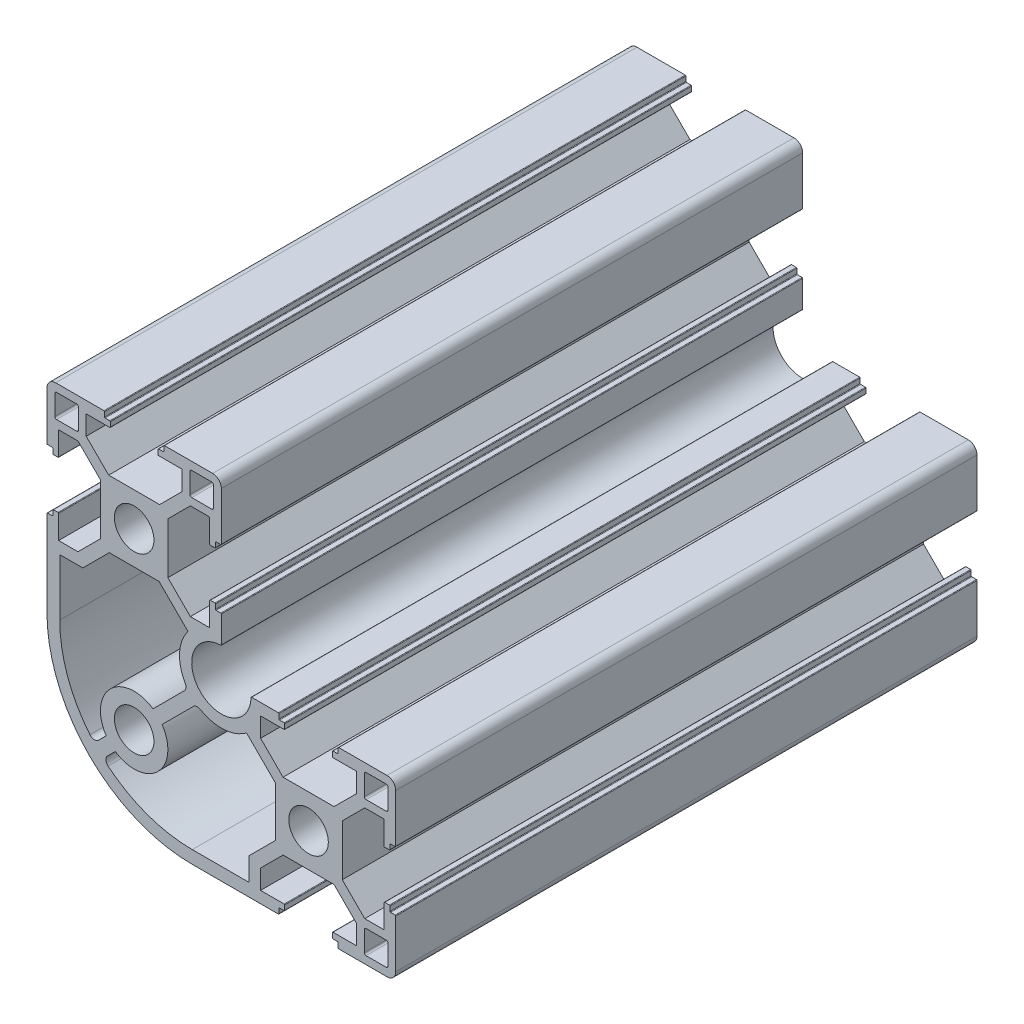
SolidWorks part; units mm, degrees
ref_plane "前视基准面" through (0, 0, 0) normal (0, 0, 1) x (1, 0, 0)
ref_plane "上视基准面" through (0, 0, 0) normal (0, 1, 0) x (1, 0, 0)
ref_plane "右视基准面" through (0, 0, 0) normal (1, 0, 0) x (0, 0, -1)
sketch "草图1" plane through (0, 0, 0) normal (0, 0, 1) x (1, 0, 0)
  line B0 (18.3418, 53.7695) -> (14.8918, 53.7695)
  line B1 (14.5918, 54.0695) -> (14.5918, 57.5195)
  line B2 (14.8918, 57.8195) -> (18.3418, 57.8195)
  line B3 (18.6418, 57.5195) -> (18.6418, 54.0695)
  line B4 (-8.6582, 54.0695) -> (-8.6582, 57.5195)
  line B5 (-8.3582, 57.8195) -> (-4.9082, 57.8195)
  line B6 (-4.6082, 57.5195) -> (-4.6082, 54.0695)
  line B7 (-4.9082, 53.7695) -> (-8.3582, 53.7695)
  line B8 (13.6091, 24.3425) -> (8.2408, 18.9742)
  line B9 (0.1872, 10.9206) -> (-1.1292, 9.6041)
  line B10 (-7.8082, 24.1695) -> (-7.8082, 33.9195)
  line B11 (-7.8082, 33.9195) -> (-3.844, 33.9195)
  line B12 (-3.844, 33.9195) -> (0.706, 38.4695)
  line B13 (0.706, 38.4695) -> (9.2776, 38.4695)
  line B14 (9.2776, 38.4695) -> (14.2429, 33.5043)
  line B15 (24.3265, 23.4206) -> (29.2918, 18.4553)
  line B16 (29.2918, 18.4553) -> (29.2918, 9.8838)
  line B17 (29.2918, 9.8838) -> (24.7418, 5.3338)
  line B18 (24.7418, 5.3338) -> (24.7418, 1.3695)
  line B19 (24.7418, 1.3695) -> (14.9918, 1.3695)
  line B20 (0.4264, 8.0485) -> (1.7429, 9.3649)
  line B21 (9.7964, 17.4185) -> (15.1647, 22.7868)
  line B22 (48.3418, 0.5195) -> (44.8918, 0.5195)
  line B23 (44.5918, 0.8195) -> (44.5918, 4.2695)
  line B24 (44.8918, 4.5695) -> (48.3418, 4.5695)
  line B25 (48.6418, 4.2695) -> (48.6418, 0.8195)
  line B26 (48.3418, 23.7695) -> (44.8918, 23.7695)
  line B27 (44.5918, 24.0695) -> (44.5918, 27.5195)
  line B28 (44.8918, 27.8195) -> (48.3418, 27.8195)
  line B29 (48.6418, 27.5195) -> (48.6418, 24.0695)
  line B30 (19.9918, 34.3686) -> (19.9918, 38.9695)
  line B31 (19.8918, 39.0695) -> (19.0918, 39.0695)
  line B32 (18.9918, 39.1695) -> (18.9918, 39.9695)
  line B33 (18.8918, 40.0695) -> (18.0918, 40.0695)
  line B34 (17.9918, 39.9695) -> (17.9918, 35.9195)
  line B35 (17.9918, 35.9195) -> (14.656, 35.9195)
  line B36 (14.656, 35.9195) -> (10.7918, 39.7838)
  line B37 (10.7918, 39.7838) -> (10.7918, 48.5553)
  line B38 (10.7918, 48.5553) -> (14.656, 52.4195)
  line B39 (14.656, 52.4195) -> (17.9918, 52.4195)
  line B40 (17.9918, 52.4195) -> (17.9918, 48.3695)
  line B41 (18.0918, 48.2695) -> (18.8918, 48.2695)
  line B42 (18.9918, 48.3695) -> (18.9918, 49.1695)
  line B43 (19.0918, 49.2695) -> (19.8918, 49.2695)
  line B44 (19.9918, 49.3695) -> (19.9918, 57.6695)
  line B45 (18.4918, 59.1695) -> (10.1918, 59.1695)
  line B46 (10.0918, 59.0695) -> (10.0918, 58.2695)
  line B47 (9.9918, 58.1695) -> (9.1918, 58.1695)
  line B48 (9.0918, 58.0695) -> (9.0918, 57.2695)
  line B49 (9.1918, 57.1695) -> (13.2418, 57.1695)
  line B50 (13.2418, 57.1695) -> (13.2418, 53.8338)
  line B51 (13.2418, 53.8338) -> (9.3776, 49.9695)
  line B52 (9.3776, 49.9695) -> (0.606, 49.9695)
  line B53 (0.606, 49.9695) -> (-3.2582, 53.8338)
  line B54 (-3.2582, 53.8338) -> (-3.2582, 57.1695)
  line B55 (-3.2582, 57.1695) -> (0.7918, 57.1695)
  line B56 (0.8918, 57.2695) -> (0.8918, 58.0695)
  line B57 (0.7918, 58.1695) -> (-0.0082, 58.1695)
  line B58 (-0.1082, 58.2695) -> (-0.1082, 59.0695)
  line B59 (-0.2082, 59.1695) -> (-8.5082, 59.1695)
  line B60 (-10.0082, 57.6695) -> (-10.0082, 49.3695)
  line B61 (-9.9082, 49.2695) -> (-9.1082, 49.2695)
  line B62 (-9.0082, 49.1695) -> (-9.0082, 48.3695)
  line B63 (-8.9082, 48.2695) -> (-8.1082, 48.2695)
  line B64 (-8.0082, 48.3695) -> (-8.0082, 52.4195)
  line B65 (-8.0082, 52.4195) -> (-4.6724, 52.4195)
  line B66 (-4.6724, 52.4195) -> (-0.8082, 48.5553)
  line B67 (-0.8082, 48.5553) -> (-0.8082, 39.7838)
  line B68 (-0.8082, 39.7838) -> (-4.6724, 35.9195)
  line B69 (-4.6724, 35.9195) -> (-8.0082, 35.9195)
  line B70 (-8.0082, 35.9195) -> (-8.0082, 39.9695)
  line B71 (-8.1082, 40.0695) -> (-8.9082, 40.0695)
  line B72 (-9.0082, 39.9695) -> (-9.0082, 39.1695)
  line B73 (-9.1082, 39.0695) -> (-9.9082, 39.0695)
  line B74 (-10.0082, 38.9695) -> (-10.0082, 24.1695)
  line B75 (14.9918, -0.8305) -> (29.7918, -0.8305)
  line B76 (29.8918, -0.7305) -> (29.8918, 0.0695)
  line B77 (29.9918, 0.1695) -> (30.7918, 0.1695)
  line B78 (30.8918, 0.2695) -> (30.8918, 1.0695)
  line B79 (30.7918, 1.1695) -> (26.7418, 1.1695)
  line B80 (26.7418, 1.1695) -> (26.7418, 4.5053)
  line B81 (26.7418, 4.5053) -> (30.606, 8.3695)
  line B82 (30.606, 8.3695) -> (39.3776, 8.3695)
  line B83 (39.3776, 8.3695) -> (43.2418, 4.5053)
  line B84 (43.2418, 4.5053) -> (43.2418, 1.1695)
  line B85 (43.2418, 1.1695) -> (39.1918, 1.1695)
  line B86 (39.0918, 1.0695) -> (39.0918, 0.2695)
  line B87 (39.1918, 0.1695) -> (39.9918, 0.1695)
  line B88 (40.0918, 0.0695) -> (40.0918, -0.7305)
  line B89 (40.1918, -0.8305) -> (48.4918, -0.8305)
  line B90 (49.9918, 0.6695) -> (49.9918, 8.9695)
  line B91 (49.8918, 9.0695) -> (49.0918, 9.0695)
  line B92 (48.9918, 9.1695) -> (48.9918, 9.9695)
  line B93 (48.8918, 10.0695) -> (48.0918, 10.0695)
  line B94 (47.9918, 9.9695) -> (47.9918, 5.9195)
  line B95 (47.9918, 5.9195) -> (44.656, 5.9195)
  line B96 (44.656, 5.9195) -> (40.7918, 9.7838)
  line B97 (40.7918, 9.7838) -> (40.7918, 18.5553)
  line B98 (40.7918, 18.5553) -> (44.656, 22.4195)
  line B99 (44.656, 22.4195) -> (47.9918, 22.4195)
  line B100 (47.9918, 22.4195) -> (47.9918, 18.3695)
  line B101 (48.0918, 18.2695) -> (48.8918, 18.2695)
  line B102 (48.9918, 18.3695) -> (48.9918, 19.1695)
  line B103 (49.0918, 19.2695) -> (49.8918, 19.2695)
  line B104 (49.9918, 19.3695) -> (49.9918, 27.6695)
  line B105 (48.4918, 29.1695) -> (40.1918, 29.1695)
  line B106 (40.0918, 29.0695) -> (40.0918, 28.2695)
  line B107 (39.9918, 28.1695) -> (39.1918, 28.1695)
  line B108 (39.0918, 28.0695) -> (39.0918, 27.2695)
  line B109 (39.1918, 27.1695) -> (43.2418, 27.1695)
  line B110 (43.2418, 27.1695) -> (43.2418, 23.8338)
  line B111 (43.2418, 23.8338) -> (39.3776, 19.9695)
  line B112 (39.3776, 19.9695) -> (30.606, 19.9695)
  line B113 (30.606, 19.9695) -> (26.7418, 23.8338)
  line B114 (26.7418, 23.8338) -> (26.7418, 27.1695)
  line B115 (26.7418, 27.1695) -> (30.7918, 27.1695)
  line B116 (30.8918, 27.2695) -> (30.8918, 28.0695)
  line B117 (30.7918, 28.1695) -> (29.9918, 28.1695)
  line B118 (29.8918, 28.2695) -> (29.8918, 29.0695)
  line B119 (29.7918, 29.1695) -> (25.1909, 29.1695)
  arc B120 (18.3418, 53.7695) -> (18.6418, 54.0695) centre (18.3418, 54.0695) ccw
  arc B121 (14.5918, 54.0695) -> (14.8918, 53.7695) centre (14.8918, 54.0695) ccw
  arc B122 (14.8918, 57.8195) -> (14.5918, 57.5195) centre (14.8918, 57.5195) ccw
  arc B123 (18.6418, 57.5195) -> (18.3418, 57.8195) centre (18.3418, 57.5195) ccw
  arc B124 (-8.6582, 54.0695) -> (-8.3582, 53.7695) centre (-8.3582, 54.0695) ccw
  arc B125 (-8.3582, 57.8195) -> (-8.6582, 57.5195) centre (-8.3582, 57.5195) ccw
  arc B126 (-4.6082, 57.5195) -> (-4.9082, 57.8195) centre (-4.9082, 57.5195) ccw
  arc B127 (-4.9082, 53.7695) -> (-4.6082, 54.0695) centre (-4.9082, 54.0695) ccw
  circle B128 centre (4.9918, 44.1695) radius 3.4
  circle B129 centre (4.9918, 14.1695) radius 3.4
  arc B130 (14.2429, 33.5043) -> (13.7666, 25.552) centre (19.9918, 29.1695) ccw
  arc B131 (13.6091, 24.3425) -> (13.7666, 25.552) centre (12.902, 25.0496) ccw
  arc B132 (8.2408, 18.9742) -> (0.1872, 10.9206) centre (4.9918, 14.1695) ccw
  arc B133 (-2.6083, 9.6755) -> (-1.1292, 9.6041) centre (-1.8363, 10.3112) ccw
  arc B134 (-7.8082, 24.1695) -> (-2.6083, 9.6755) centre (14.9918, 24.1695) ccw
  arc B135 (16.3743, 22.9443) -> (24.3265, 23.4206) centre (19.9918, 29.1695) ccw
  arc B136 (0.4978, 6.5695) -> (14.9918, 1.3695) centre (14.9918, 24.1695) ccw
  arc B137 (0.4264, 8.0485) -> (0.4978, 6.5695) centre (1.1335, 7.3414) ccw
  arc B138 (1.7429, 9.3649) -> (9.7964, 17.4185) centre (4.9918, 14.1695) ccw
  arc B139 (16.3743, 22.9443) -> (15.1647, 22.7868) centre (15.8718, 22.0797) ccw
  circle B140 centre (34.9918, 14.1695) radius 3.4
  arc B141 (48.3418, 0.5195) -> (48.6418, 0.8195) centre (48.3418, 0.8195) ccw
  arc B142 (44.5918, 0.8195) -> (44.8918, 0.5195) centre (44.8918, 0.8195) ccw
  arc B143 (44.8918, 4.5695) -> (44.5918, 4.2695) centre (44.8918, 4.2695) ccw
  arc B144 (48.6418, 4.2695) -> (48.3418, 4.5695) centre (48.3418, 4.2695) ccw
  arc B145 (48.3418, 23.7695) -> (48.6418, 24.0695) centre (48.3418, 24.0695) ccw
  arc B146 (44.5918, 24.0695) -> (44.8918, 23.7695) centre (44.8918, 24.0695) ccw
  arc B147 (44.8918, 27.8195) -> (44.5918, 27.5195) centre (44.8918, 27.5195) ccw
  arc B148 (48.6418, 27.5195) -> (48.3418, 27.8195) centre (48.3418, 27.5195) ccw
  arc B149 (19.8938, 34.2686) -> (25.0909, 29.0715) centre (19.9918, 29.1695) ccw
  arc B150 (19.8938, 34.2686) -> (19.9918, 34.3686) centre (19.8918, 34.3686) ccw
  arc B151 (19.9918, 38.9695) -> (19.8918, 39.0695) centre (19.8918, 38.9695) ccw
  arc B152 (18.9918, 39.1695) -> (19.0918, 39.0695) centre (19.0918, 39.1695) ccw
  arc B153 (18.9918, 39.9695) -> (18.8918, 40.0695) centre (18.8918, 39.9695) ccw
  arc B154 (18.0918, 40.0695) -> (17.9918, 39.9695) centre (18.0918, 39.9695) ccw
  arc B155 (17.9918, 48.3695) -> (18.0918, 48.2695) centre (18.0918, 48.3695) ccw
  arc B156 (18.8918, 48.2695) -> (18.9918, 48.3695) centre (18.8918, 48.3695) ccw
  arc B157 (19.0918, 49.2695) -> (18.9918, 49.1695) centre (19.0918, 49.1695) ccw
  arc B158 (19.8918, 49.2695) -> (19.9918, 49.3695) centre (19.8918, 49.3695) ccw
  arc B159 (19.9918, 57.6695) -> (18.4918, 59.1695) centre (18.4918, 57.6695) ccw
  arc B160 (10.1918, 59.1695) -> (10.0918, 59.0695) centre (10.1918, 59.0695) ccw
  arc B161 (9.9918, 58.1695) -> (10.0918, 58.2695) centre (9.9918, 58.2695) ccw
  arc B162 (9.1918, 58.1695) -> (9.0918, 58.0695) centre (9.1918, 58.0695) ccw
  arc B163 (9.0918, 57.2695) -> (9.1918, 57.1695) centre (9.1918, 57.2695) ccw
  arc B164 (0.7918, 57.1695) -> (0.8918, 57.2695) centre (0.7918, 57.2695) ccw
  arc B165 (0.8918, 58.0695) -> (0.7918, 58.1695) centre (0.7918, 58.0695) ccw
  arc B166 (-0.1082, 58.2695) -> (-0.0082, 58.1695) centre (-0.0082, 58.2695) ccw
  arc B167 (-0.1082, 59.0695) -> (-0.2082, 59.1695) centre (-0.2082, 59.0695) ccw
  arc B168 (-8.5082, 59.1695) -> (-10.0082, 57.6695) centre (-8.5082, 57.6695) ccw
  arc B169 (-10.0082, 49.3695) -> (-9.9082, 49.2695) centre (-9.9082, 49.3695) ccw
  arc B170 (-9.0082, 49.1695) -> (-9.1082, 49.2695) centre (-9.1082, 49.1695) ccw
  arc B171 (-9.0082, 48.3695) -> (-8.9082, 48.2695) centre (-8.9082, 48.3695) ccw
  arc B172 (-8.1082, 48.2695) -> (-8.0082, 48.3695) centre (-8.1082, 48.3695) ccw
  arc B173 (-8.0082, 39.9695) -> (-8.1082, 40.0695) centre (-8.1082, 39.9695) ccw
  arc B174 (-8.9082, 40.0695) -> (-9.0082, 39.9695) centre (-8.9082, 39.9695) ccw
  arc B175 (-9.1082, 39.0695) -> (-9.0082, 39.1695) centre (-9.1082, 39.1695) ccw
  arc B176 (-9.9082, 39.0695) -> (-10.0082, 38.9695) centre (-9.9082, 38.9695) ccw
  arc B177 (-10.0082, 24.1695) -> (14.9918, -0.8305) centre (14.9918, 24.1695) ccw
  arc B178 (29.7918, -0.8305) -> (29.8918, -0.7305) centre (29.7918, -0.7305) ccw
  arc B179 (29.9918, 0.1695) -> (29.8918, 0.0695) centre (29.9918, 0.0695) ccw
  arc B180 (30.7918, 0.1695) -> (30.8918, 0.2695) centre (30.7918, 0.2695) ccw
  arc B181 (30.8918, 1.0695) -> (30.7918, 1.1695) centre (30.7918, 1.0695) ccw
  arc B182 (39.1918, 1.1695) -> (39.0918, 1.0695) centre (39.1918, 1.0695) ccw
  arc B183 (39.0918, 0.2695) -> (39.1918, 0.1695) centre (39.1918, 0.2695) ccw
  arc B184 (40.0918, 0.0695) -> (39.9918, 0.1695) centre (39.9918, 0.0695) ccw
  arc B185 (40.0918, -0.7305) -> (40.1918, -0.8305) centre (40.1918, -0.7305) ccw
  arc B186 (48.4918, -0.8305) -> (49.9918, 0.6695) centre (48.4918, 0.6695) ccw
  arc B187 (49.9918, 8.9695) -> (49.8918, 9.0695) centre (49.8918, 8.9695) ccw
  arc B188 (48.9918, 9.1695) -> (49.0918, 9.0695) centre (49.0918, 9.1695) ccw
  arc B189 (48.9918, 9.9695) -> (48.8918, 10.0695) centre (48.8918, 9.9695) ccw
  arc B190 (48.0918, 10.0695) -> (47.9918, 9.9695) centre (48.0918, 9.9695) ccw
  arc B191 (47.9918, 18.3695) -> (48.0918, 18.2695) centre (48.0918, 18.3695) ccw
  arc B192 (48.8918, 18.2695) -> (48.9918, 18.3695) centre (48.8918, 18.3695) ccw
  arc B193 (49.0918, 19.2695) -> (48.9918, 19.1695) centre (49.0918, 19.1695) ccw
  arc B194 (49.8918, 19.2695) -> (49.9918, 19.3695) centre (49.8918, 19.3695) ccw
  arc B195 (49.9918, 27.6695) -> (48.4918, 29.1695) centre (48.4918, 27.6695) ccw
  arc B196 (40.1918, 29.1695) -> (40.0918, 29.0695) centre (40.1918, 29.0695) ccw
  arc B197 (39.9918, 28.1695) -> (40.0918, 28.2695) centre (39.9918, 28.2695) ccw
  arc B198 (39.1918, 28.1695) -> (39.0918, 28.0695) centre (39.1918, 28.0695) ccw
  arc B199 (39.0918, 27.2695) -> (39.1918, 27.1695) centre (39.1918, 27.2695) ccw
  arc B200 (30.7918, 27.1695) -> (30.8918, 27.2695) centre (30.7918, 27.2695) ccw
  arc B201 (30.8918, 28.0695) -> (30.7918, 28.1695) centre (30.7918, 28.0695) ccw
  arc B202 (29.8918, 28.2695) -> (29.9918, 28.1695) centre (29.9918, 28.2695) ccw
  arc B203 (29.8918, 29.0695) -> (29.7918, 29.1695) centre (29.7918, 29.0695) ccw
  arc B204 (25.1909, 29.1695) -> (25.0909, 29.0715) centre (25.1909, 29.0695) ccw
sketch_block_instance "A$C09356BA4-1"
sketch_block "A$C09356BA4"
extrude "凸台-拉伸1" add sketch "草图1" along normal blind 100
